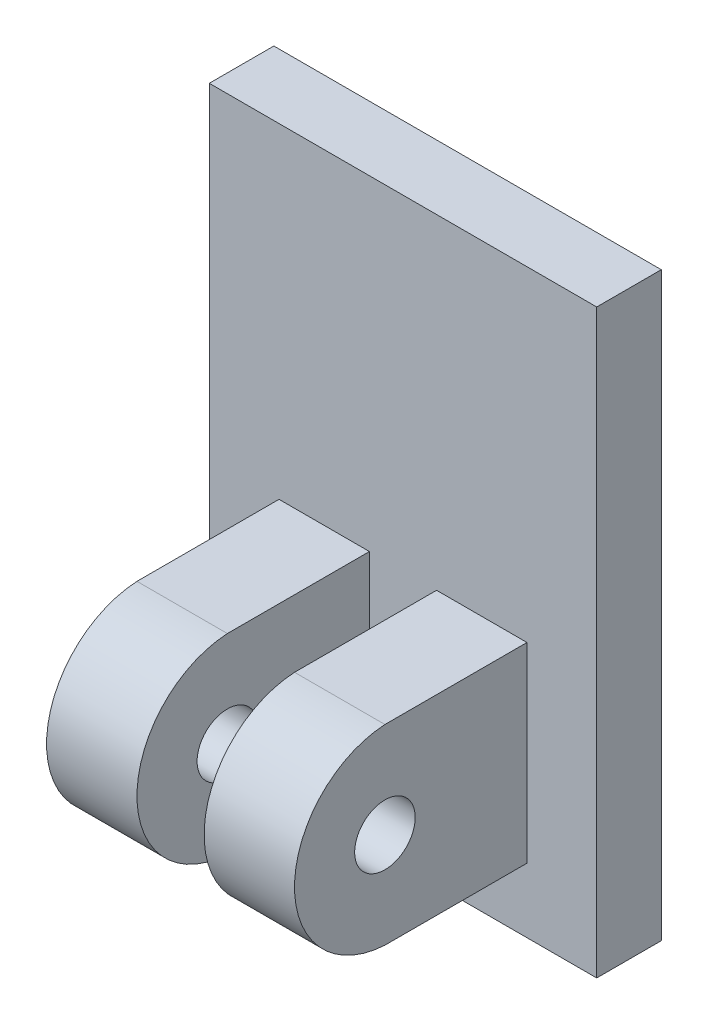
SolidWorks part; units mm, degrees
ref_plane "Alzado" through (0, 0, 0) normal (0, 0, 1) x (1, 0, 0)
ref_plane "Planta" through (0, 0, 0) normal (0, 1, 0) x (1, 0, 0)
ref_plane "Vista lateral" through (0, 0, 0) normal (1, 0, 0) x (0, 0, -1)
sketch "Croquis1" plane through (0, 0, 0) normal (0, 0, 1) x (1, 0, 0)
  line L1 (0, 0) -> (30, 0)
  line L2 (0, 0) -> (0, 45)
  line L3 (0, 45) -> (30, 45)
  line L4 (30, 0) -> (30, 45)
  line L5 (30, 0) -> (15, 0)
  line L6 (30, 0) -> (30, 45)
  line L7 (30, 45) -> (15, 45)
  line L8 (15, 0) -> (15, 45)
  line L9 (17.5, 19.8) -> (24.5, 19.8)
  line L10 (17.5, 19.8) -> (17.5, 5)
  line L11 (17.5, 5) -> (24.5, 5)
  line L12 (24.5, 19.8) -> (24.5, 5)
  line L13 (5.5, 19.8) -> (12.5, 19.8)
  line L14 (5.5, 19.8) -> (5.5, 5)
  line L15 (5.5, 5) -> (12.5, 5)
  line L16 (12.5, 19.8) -> (12.5, 5)
  point P15 (21, 19.8)
  dimension "D1" = 30
  dimension "D2" = 45
  dimension "D3" = 7
  dimension "D4" = 7
  dimension "D5" = 2.5
  dimension "D6" = 2.5
  dimension "D7" = 14.8
  dimension "D8" = 5
  dimension "D9" = 5
  dimension "D10" = 14.8
  dimension "D11" = 25.2
extrude "Saliente-Extruir1" add sketch "Croquis1" along normal blind 5 contours L1 L8 L3 L2 L13 L16 L15 L14 | L8 L1 L4 L3 L9 L12 L11 L10 | L12 L9 L10 L11 | L16 L13 L14 L15
sketch "Croquis2" plane through (0, 0, 5) normal (0, 0, 1) x (1, 0, 0)
  line L0 (0, 0) -> (30, 0) construction
  line L1 (0, 45) -> (15, 45)
  line L2 (0, 45) -> (0, 0)
  line L3 (0, 0) -> (15, 0)
  line L4 (15, 45) -> (15, 0)
  line L6 (5.4, 19.8) -> (12.4, 19.8)
  line L7 (5.4, 19.8) -> (5.4, 5)
  line L8 (5.4, 5) -> (12.4, 5)
  line L9 (12.4, 19.8) -> (12.4, 5)
  line L10 (17.6, 19.8) -> (24.6, 19.8)
  line L11 (17.6, 19.8) -> (17.6, 5)
  line L12 (17.6, 5) -> (24.6, 5)
  line L13 (24.6, 19.8) -> (24.6, 5)
  dimension "D1" = 14.8
  dimension "D2" = 5
  dimension "D3" = 5
  dimension "D4" = 14.8
  dimension "D5" = 2.6
  dimension "D6" = 5.2
  dimension "D7" = 7
  dimension "D8" = 7
extrude "Saliente-Extruir4" add sketch "Croquis2" along normal blind 18 contours L7 L6 L9 L8 | L11 L10 L13 L12
sketch "Croquis4" plane through (5.4, 0, 0) normal (-1, 0, 0) x (0, 0, 1)
  line L0 (5, 19.8) -> (5, 5) construction
  line L1 (5, 12.4) -> (23, 12.4)
  line L2 (5, 12.4) -> (5, 5)
  line L3 (5, 5) -> (23, 5)
  line L4 (23, 12.4) -> (23, 5)
  line L6 (23, 19.8) -> (16, 19.8)
  line L7 (23, 19.8) -> (23, 5)
  line L8 (23, 5) -> (16, 5)
  line L9 (16, 19.8) -> (16, 5)
  line L10 (5, 5) -> (16, 5)
  line L11 (5, 5) -> (5, 12.4)
  line L12 (5, 12.4) -> (16, 12.4)
  line L13 (16, 5) -> (16, 12.4)
  circle A0 centre (16, 12.4) radius 2.3438
  arc A1 (23, 12.4) -> (16, 19.8) centre (15.5886, 12.4) ccw
  arc A2 (23, 12.4) -> (16, 5) centre (15.5886, 12.4) cw
  line M9 (23, 5) -> (23, 19.8)
  line M10 (23, 19.8) -> (5, 19.8)
  dimension "D3" = 4.6875
  dimension "D1" = 7
  dimension "D2" = 11
extrude "Cortar-Extruir3" cut sketch "Croquis4" against normal through all and the other way through all contours L1 A0 L9 | L9 A0 L12 | L12 A0 L9 | L9 A0 L1 | A1 M9 M10 | A2 L3 M9
